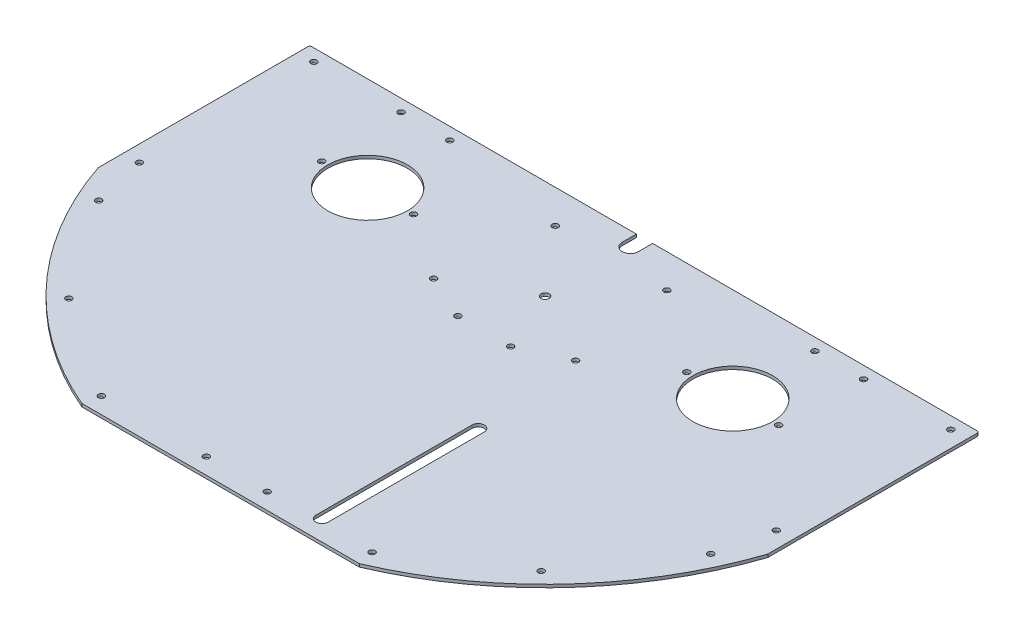
SolidWorks part; units mm, degrees
material "3.3535 (EN-AW 5754)"
ref_plane "Plan de face" through (0, 0, 0) normal (0, 0, 1) x (1, 0, 0)
ref_plane "Plan de dessus" through (0, 0, 0) normal (0, 1, 0) x (1, 0, 0)
ref_plane "Plan de droite" through (0, 0, 0) normal (1, 0, 0) x (0, 0, -1)
sketch "Esquisse1" plane through (0, 0, 0) normal (0, 1, 0) x (1, 0, 0)
  line L1 (0, 49) -> (165, 49)
  line L2 (0, 49) -> (0, -160)
  line L3 (0, -160) -> (68.3813, -160)
  line L4 (165, 49) -> (165, -55.2359)
  arc A0 (68.3813, -160) -> (165, -55.2359) centre (0, 0) ccw
  dimension "D4" = 348
  dimension "D1" = 49
  dimension "D2" = 165
  dimension "D3" = 160
extrude "Boss.-Extru.1" add sketch "Esquisse1" along normal blind 1.5
mirror "Symétrie1" about plane through (0, 1.5, -49) normal (1, 0, 0) of bodies 101 102
sketch "Esquisse7" plane through (0, 1.5, 0) normal (0, 1, 0) x (1, 0, 0)
  line L0 (-68.3813, -160) -> (68.3813, -160) construction
  line L1 (-165, -55.2359) -> (-165, 49) construction
  line L2 (165, -55.2359) -> (165, 49) construction
  line L3 (0, -0.825) -> (0, 0.825) construction
  line L4 (165, 49) -> (-165, 49) construction
  circle A0 centre (-157, -43) radius 1.5
  circle A1 centre (157, -43) radius 1.5
  circle A5 centre (157, 43) radius 1.5
  circle A13 centre (-157, 43) radius 1.5
  circle A14 centre (-114, 43) radius 1.5
  circle A15 centre (-90, 43) radius 1.5
  circle A16 centre (90, 43) radius 1.5
  circle A17 centre (114, 43) radius 1.5
  dimension "D5" = 3
  dimension "D3" = 43
  dimension "D4" = 86
  dimension "D8" = 117
  dimension "D9" = 8
  dimension "D6" = 8
  dimension "D7" = 24
  dimension "D10" = 180
  dimension "D11" = 6
  dimension "D12" = 90
  dimension "D13" = 114
  dimension "D1" = 2
  dimension "D2" = 2
extrude "Enlèv. mat.-Extru.5" cut sketch "Esquisse7" against normal through all
sketch "Esquisse8" plane through (0, 1.5, 0) normal (0, 1, 0) x (1, 0, 0)
  line L1 (0, -0.825) -> (0, 0.825) construction
  line L2 (-112.6274, 2.5) -> (-67.3726, 2.5) construction
  line L3 (-112.6274, 2.5) -> (-90, 25.1274) construction
  line L4 (-90, 25.1274) -> (-67.3726, 2.5) construction
  circle A1 centre (-90, 2.5) radius 19.6274
  circle A5 centre (-112.6274, 2.5) radius 1.5
  circle A6 centre (-67.3726, 2.5) radius 1.5
  circle A7 centre (112.6274, 2.5) radius 1.5
  circle A8 centre (67.3726, 2.5) radius 1.5
  circle A9 centre (-112.6274, 2.5) radius 3 construction
  circle A10 centre (90, 2.5) radius 19.6274
  dimension "D1" = 39.2548
  dimension "D2" = 3
  dimension "D3" = 45.2548
  dimension "D7" = 6
  dimension "D4" = 180
  dimension "D5" = 2.5
  dimension "D6" = 32
extrude "Enlèv. mat.-Extru.6" cut sketch "Esquisse8" against normal through all
sketch "Esquisse9" plane through (0, 1.5, 0) normal (0, 1, 0) x (1, 0, 0)
  line L0 (0, 49) -> (0, 42) construction
  line L1 (0, -0.825) -> (0, 0.825) construction
  line L2 (165, 49) -> (-165, 49) construction
  line L3 (4, 49) -> (4, 42)
  line L4 (-4, 49) -> (-4, 42)
  circle A1 centre (27.5, 32.5) radius 1.5
  circle A2 centre (-13, -30) radius 1.5
  circle A3 centre (35, -20) radius 1.5
  circle A4 centre (-27.5, 32.5) radius 1.5
  circle A5 centre (0, 0) radius 2
  arc A6 (4, 49) -> (-4, 49) centre (0, 49) ccw
  arc A7 (-4, 42) -> (4, 42) centre (0, 42) ccw
  circle A8 centre (-35, -20) radius 1.5
  circle A9 centre (13, -30) radius 1.5
  point P17 (0, 45.5)
  dimension "D1" = 3
  dimension "D2" = 48
  dimension "D3" = 10
  dimension "D4" = 55
  dimension "D5" = 32.5
  dimension "D8" = 4
  dimension "D11" = 42
  dimension "D6" = 30
  dimension "D7" = 13
  dimension "D9" = 8
  dimension "D10" = 7
extrude "Enlèv. mat.-Extru.7" cut sketch "Esquisse9" against normal through all
sketch "Esquisse10" plane through (0, 1.5, 0) normal (0, 1, 0) x (1, 0, 0)
  line L0 (40, -73) -> (40, -150) construction
  line L1 (43, -73) -> (43, -150)
  line L2 (37, -73) -> (37, -150)
  arc A0 (43, -73) -> (37, -73) centre (40, -73) ccw
  arc A1 (37, -150) -> (43, -150) centre (40, -150) ccw
  point P2 (40, -111.5)
  dimension "D2" = 40
  dimension "D3" = 150
  dimension "D1" = 73
  dimension "D4" = 6
extrude "Enlèv. mat.-Extru.8" cut sketch "Esquisse10" against normal through all
fillet "Congé1" radius 1 2 edges at (165, 0.75, -49) (-165, 0.75, -49)
sketch "Esquisse11" plane through (0, 1.5, 0) normal (0, 1, 0) x (1, 0, 0)
  line L0 (0, -0.825) -> (0, 0.825) construction
  line L1 (-68.3813, -160) -> (68.3813, -160) construction
  circle A0 centre (-150.8698, -69.241) radius 1.5
  circle A1 centre (-116.4, -118.3514) radius 1.5
  circle A2 centre (-66.7233, -152) radius 1.5
  circle A3 centre (66.7233, -152) radius 1.5
  circle A4 centre (116.4, -118.3514) radius 1.5
  circle A5 centre (150.8698, -69.241) radius 1.5
  circle A6 centre (-15, -152) radius 1.5
  circle A7 centre (0, 0) radius 166 construction
  arc A8 (-165, -55.2359) -> (-68.3813, -160) centre (0, 0) ccw construction
  circle A9 centre (15, -152) radius 1.5
  dimension "D1" = 8
  dimension "D2" = 8
  dimension "D3" = 3
  dimension "D4" = 60
  dimension "D5" = 60
  dimension "D6" = 51.7233
  dimension "D7" = 30
extrude "Enlèv. mat.-Extru.9" cut sketch "Esquisse11" against normal through all
equation "\"D3@Esquisse7\"=\"D4@Esquisse7\"*(\"D2@Esquisse7\"-1)/2"
equation "\"D6@Esquisse7\"=\"D9@Esquisse7\""
